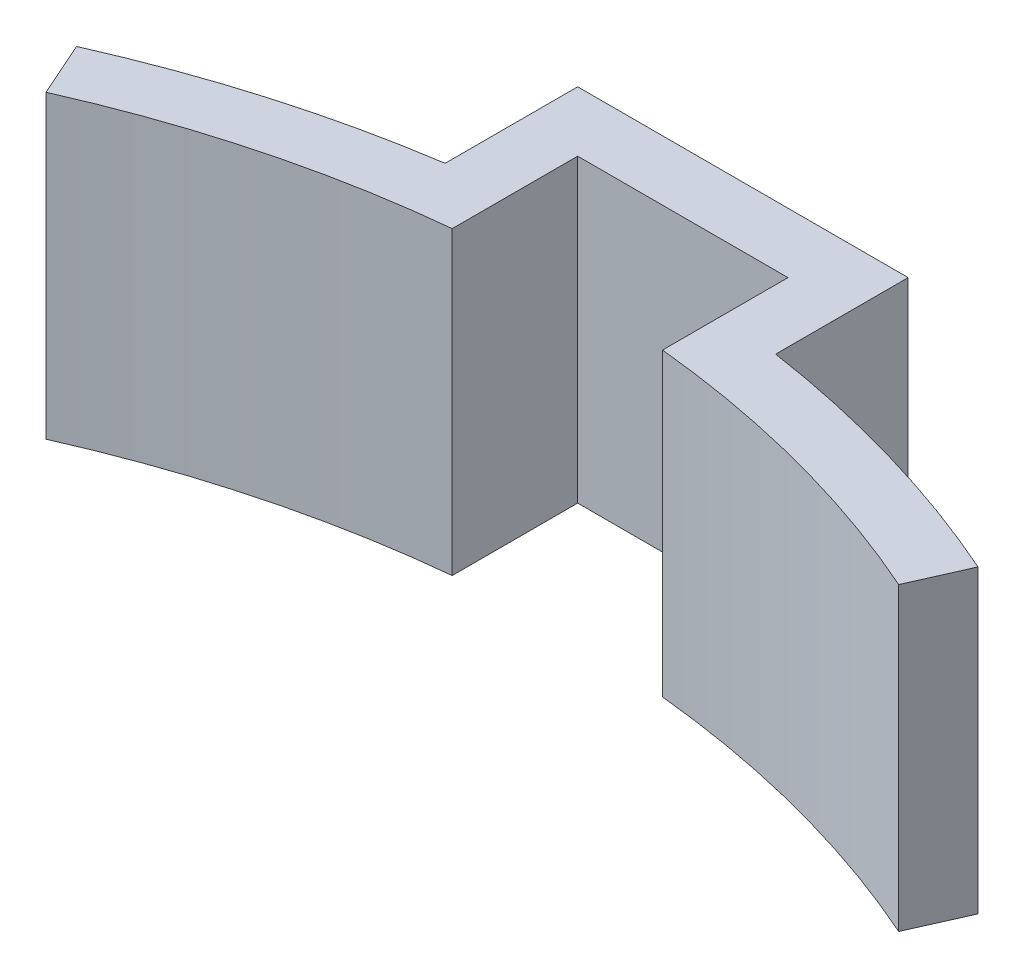
SolidWorks part; units mm, degrees
ref_plane "Front Plane" through (0, 0, 0) normal (0, 0, 1) x (1, 0, 0)
ref_plane "Top Plane" through (0, 0, 0) normal (0, 1, 0) x (1, 0, 0)
ref_plane "Right Plane" through (0, 0, 0) normal (1, 0, 0) x (0, 0, -1)
sketch "Sketch1" plane through (0, 0, 0) normal (0, 1, 0) x (1, 0, 0)
  line L0 (-14.1892, 31.9948) -> (-15, 33.8231)
  line L2 (-3.5, 34.8246) -> (-3.5, 39)
  line L3 (-3.5, 39) -> (3.5, 39)
  line L4 (3.5, 34.8246) -> (3.5, 39)
  line L6 (-5.5, 36.5889) -> (-5.5, 41)
  line L7 (-5.5, 41) -> (5.5, 41)
  line L8 (5.5, 36.5889) -> (5.5, 41)
  line L9 (14.1892, 31.9948) -> (15, 33.8231)
  line L10 (0, 0) -> (0, 37) construction
  arc A0 (14.1892, 31.9948) -> (3.5, 34.8246) centre (0, 0) ccw
  arc A1 (15, 33.8231) -> (5.5, 36.5889) centre (0, 0) ccw
  arc A2 (-3.5, 34.8246) -> (-14.1892, 31.9948) centre (0, 0) ccw
  arc A3 (-5.5, 36.5889) -> (-15, 33.8231) centre (0, 0) ccw
  point P11 (0, 0)
  point P14 (0, 39)
  dimension "D1" = 2
  dimension "D2" = 70
  dimension "D3" = 7
  dimension "D4" = 39
  dimension "D5" = 2
  dimension "D6" = 2
  dimension "D7" = 30
extrude "Boss-Extrude1" add sketch "Sketch1" along normal blind 10
